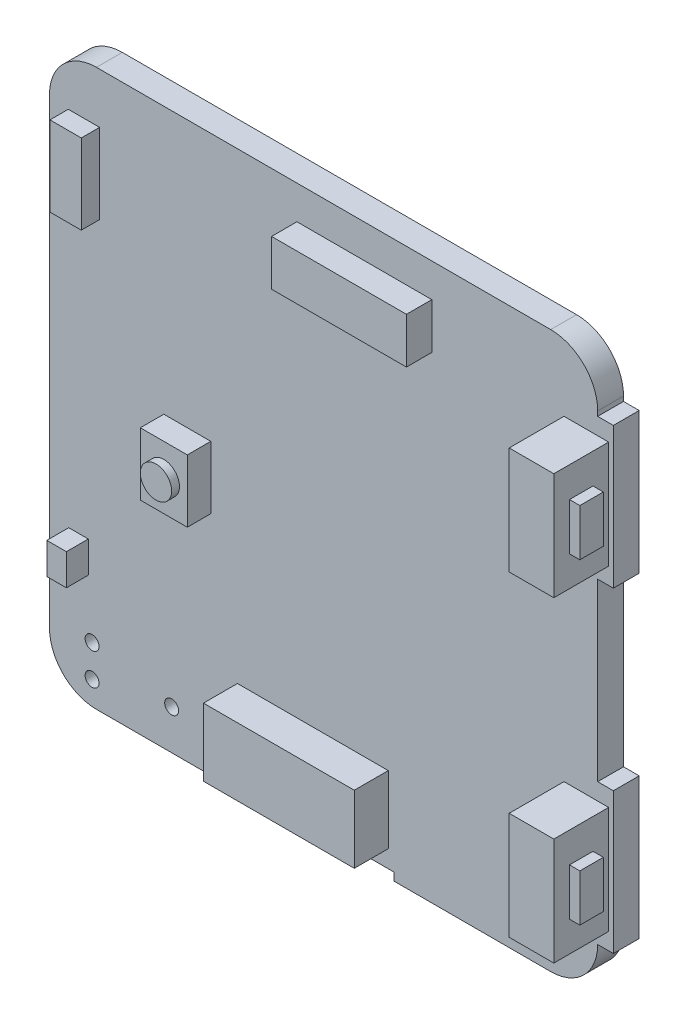
SolidWorks part; units mm, degrees
ref_plane "Front Plane" through (0, 0, 0) normal (0, 0, 1) x (1, 0, 0)
ref_plane "Top Plane" through (0, 0, 0) normal (0, 1, 0) x (1, 0, 0)
ref_plane "Right Plane" through (0, 0, 0) normal (1, 0, 0) x (0, 0, -1)
sketch "Model" plane through (0, 0, 0) normal (0, 0, 1) x (1, 0, 0)
  line L0 (3, 35.5) -> (32, 35.5)
  line L1 (35, 23.2) -> (35, 12)
  line L2 (32, 0) -> (22, 0)
  line L3 (11.1, 0) -> (3, 0)
  line L4 (35, 3) -> (36, 3)
  line L5 (36, 3) -> (36, 12)
  line L6 (36, 12) -> (35, 12)
  line L7 (35, 32.2) -> (36, 32.2)
  line L8 (36, 32.2) -> (36, 23.2)
  line L9 (36, 23.2) -> (35, 23.2)
  line L10 (0, 3) -> (0, 32.5)
  line L11 (11.1, 0) -> (11.1, 0.5)
  line L12 (11.1, 0.5) -> (22, 0.5)
  line L13 (22, 0.5) -> (22, 0)
  line L14 (35, 32.2) -> (35, 32.5)
  arc A0 (3, 35.5) -> (0, 32.5) centre (3, 32.5) ccw
  arc A1 (0, 3) -> (3, 0) centre (3, 3) ccw
  arc A2 (35, 32.5) -> (32, 35.5) centre (32, 32.5) ccw
  arc A3 (32, 0) -> (35, 3) centre (32, 3) ccw
  circle A4 centre (7.8, 2.54) radius 0.4445
  circle A5 centre (2.72, 1.524) radius 0.4445
  circle A6 centre (2.72, 3.556) radius 0.4445
  circle A7 centre (17, 32.3) radius 0.3
  circle A8 centre (23.54, 32.3) radius 0.3
  circle A9 centre (30.76, 25.494) radius 0.3
extrude "Boss-Extrude1" add sketch "Model" along normal blind 1.65
sketch "Sketch2" plane through (0, 0, 1.65) normal (0, 0, 1) x (1, 0, 0)
  line L0 (36, 23.2) -> (36, 32.2) construction
  line L1 (32.85, 31.129) -> (35.7, 31.129)
  line L2 (32.85, 31.129) -> (32.85, 24.271)
  line L3 (32.85, 24.271) -> (35.7, 24.271)
  line L4 (35.7, 31.129) -> (35.7, 24.271)
  line L5 (32.85, 10.929) -> (35.7, 10.929)
  line L6 (32.85, 10.929) -> (32.85, 4.071)
  line L7 (32.85, 4.071) -> (35.7, 4.071)
  line L8 (35.7, 10.929) -> (35.7, 4.071)
  line L10 (36, 3) -> (36, 12) construction
  point P12 (36, 27.7)
  point P13 (32.85, 27.7)
  point P14 (36, 7.5)
  point P15 (35.7, 7.5)
  dimension "D1" = 6.858
  dimension "D2" = 2.85
  dimension "D3" = 0.3
extrude "Boss-Extrude2" add sketch "Sketch2" along normal blind 3.5
sketch "Sketch3" plane through (35.7, 0, 0) normal (1, 0, 0) x (0, 0, -1)
  line L0 (-5.15, 4.071) -> (-5.15, 10.929) construction
  line L1 (-4.15, 29.2) -> (-2.65, 29.2)
  line L2 (-4.15, 29.2) -> (-4.15, 26.2)
  line L3 (-4.15, 26.2) -> (-2.65, 26.2)
  line L4 (-2.65, 29.2) -> (-2.65, 26.2)
  line L5 (-4.15, 9) -> (-2.65, 9)
  line L6 (-4.15, 9) -> (-4.15, 6)
  line L7 (-4.15, 6) -> (-2.65, 6)
  line L8 (-2.65, 9) -> (-2.65, 6)
  line L9 (-5.15, 24.271) -> (-5.15, 31.129) construction
  line L10 (-5.15, 31.129) -> (-1.65, 31.129) construction
  point P8 (-5.15, 7.5)
  point P11 (-4.15, 7.5)
  point P14 (-5.15, 27.7)
  point P15 (-4.15, 27.7)
  point P16 (-3.4, 29.2)
  point P19 (-3.4, 31.129)
  dimension "D1" = 1.5
  dimension "D2" = 3
extrude "Boss-Extrude3" add sketch "Sketch3" along normal blind 0.66
sketch "Sketch4" plane through (0, 0, 1.65) normal (0, 0, 1) x (1, 0, 0)
  line L0 (0, 32.5) -> (0, 3) construction
  line L1 (1.23, 7.16) -> (2.48, 7.16)
  line L2 (1.23, 7.16) -> (1.23, 9.16)
  line L3 (1.23, 9.16) -> (2.48, 9.16)
  line L4 (2.48, 7.16) -> (2.48, 9.16)
  dimension "D1" = 1.23
  dimension "D2" = 2
  dimension "D3" = 1.25
  dimension "D4" = 7.16
extrude "Boss-Extrude4" add sketch "Sketch4" along normal blind 1.4
sketch "Sketch5" plane through (0, 0, 1.65) normal (0, 0, 1) x (1, 0, 0)
  line L0 (0, 32.5) -> (0, 3) construction
  line L1 (1.2, 32.28) -> (3.2, 32.28)
  line L2 (1.2, 32.28) -> (1.2, 27.18)
  line L3 (1.2, 27.18) -> (3.2, 27.18)
  line L4 (3.2, 32.28) -> (3.2, 27.18)
  line L5 (32, 35.5) -> (3, 35.5) construction
  point P8 (2.2, 32.28)
  dimension "D1" = 5.1
  dimension "D2" = 2
  dimension "D3" = 1.2
  dimension "D4" = 3.22
extrude "Boss-Extrude5" add sketch "Sketch5" along normal blind 1.17
sketch "Sketch6" plane through (0, 0, 1.65) normal (0, 0, 1) x (1, 0, 0)
  line L0 (32, 35.5) -> (3, 35.5) construction
  line L1 (15.8, 33.36) -> (24.41, 33.36)
  line L2 (15.8, 33.36) -> (15.8, 30.44)
  line L3 (15.8, 30.44) -> (24.41, 30.44)
  line L4 (24.41, 33.36) -> (24.41, 30.44)
  line L5 (0, 32.5) -> (0, 3) construction
  dimension "D1" = 8.61
  dimension "D2" = 2.92
  dimension "D3" = 2.14
  dimension "D4" = 15.8
extrude "Boss-Extrude6" add sketch "Sketch6" along normal blind 1.62
sketch "Sketch7" plane through (0, 0, 1.65) normal (0, 0, 1) x (1, 0, 0)
  line L0 (22, 0) -> (32, 0) construction
  line L1 (12, 5.93) -> (21.63, 5.93)
  line L2 (12, 5.93) -> (12, 1.61)
  line L3 (12, 1.61) -> (21.63, 1.61)
  line L4 (21.63, 5.93) -> (21.63, 1.61)
  dimension "D1" = 9.63
  dimension "D2" = 4.32
  dimension "D3" = 1.61
  dimension "D4" = 12
extrude "Boss-Extrude7" add sketch "Sketch7" along normal blind 2.17
sketch "Sketch8" plane through (0, 0, 1.65) normal (0, 0, 1) x (1, 0, 0)
  line L1 (7.3, 18.47) -> (10.3, 18.47)
  line L2 (7.3, 18.47) -> (7.3, 14.47)
  line L3 (7.3, 14.47) -> (10.3, 14.47)
  line L4 (10.3, 18.47) -> (10.3, 14.47)
  dimension "D1" = 3
  dimension "D2" = 4
  dimension "D3" = 14.47
  dimension "D4" = 7.3
extrude "Boss-Extrude8" add sketch "Sketch8" along normal blind 1.5
sketch "Sketch9" plane through (0, 0, 3.15) normal (0, 0, 1) x (1, 0, 0)
  line L1 (10.3, 14.47) -> (10.3, 18.47) construction
  line L2 (7.3, 16.47) -> (10.3, 16.47) construction
  line L3 (7.3, 18.47) -> (7.3, 14.47) construction
  circle A0 centre (8.8, 16.47) radius 1
  point P4 (0, 0)
  point P9 (8.8, 16.47)
  dimension "D1" = 2
extrude "Boss-Extrude9" add sketch "Sketch9" along normal blind 0.5
